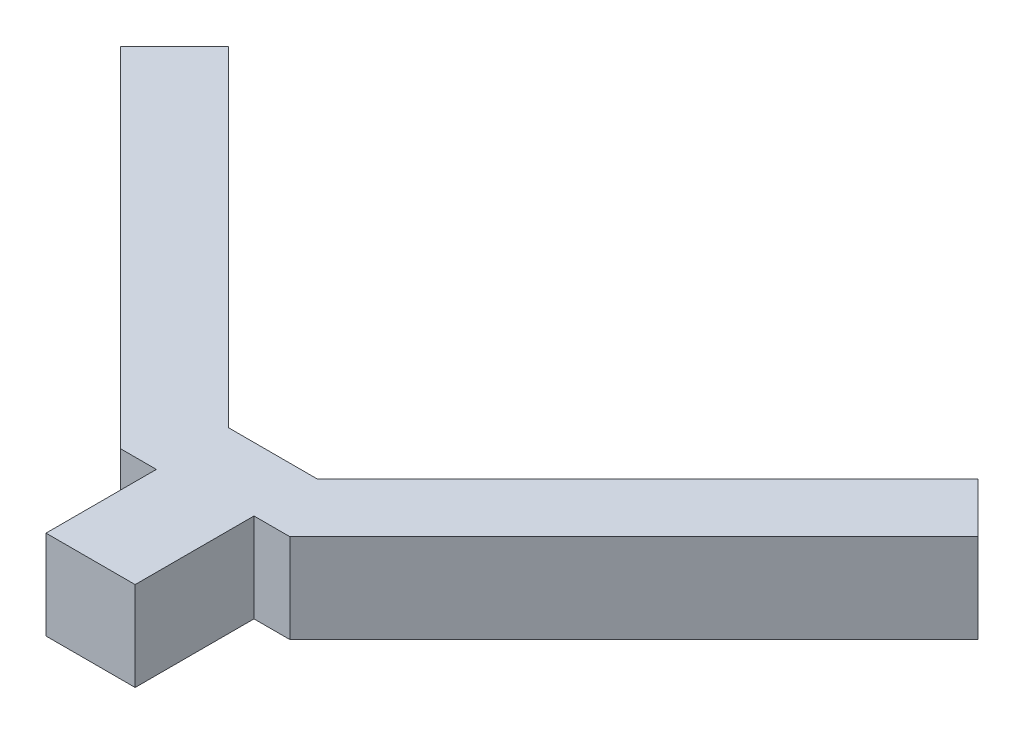
SolidWorks part; units mm, degrees
ref_plane "前视基准面" through (0, 0, 0) normal (0, 0, 1) x (1, 0, 0)
ref_plane "上视基准面" through (0, 0, 0) normal (0, 1, 0) x (1, 0, 0)
ref_plane "右视基准面" through (0, 0, 0) normal (1, 0, 0) x (0, 0, -1)
sketch "草图1" plane through (0, 0, 0) normal (0, 1, 0) x (1, 0, 0)
  line L0 (0.4355, 2.8768) -> (8.2137, 10.655)
  line L1 (8.2137, 10.655) -> (9.3865, 9.4822)
  line L2 (-1.6645, 1.1768) -> (-1.6645, -1.4232)
  line L3 (-1.6645, -1.4232) -> (0.4355, -1.4232)
  line L4 (0.4355, 1.3768) -> (0.4355, -1.4232)
  line L5 (-1.6645, 1.1768) -> (0.4355, -1.4232) construction
  line L6 (-1.6645, -1.4232) -> (0.4355, 1.3768) construction
  line L7 (-1.6645, 2.8768) -> (0.4355, 2.8768)
  line L8 (-1.6645, 2.8768) -> (-9.4427, 10.655)
  line L9 (-9.4427, 10.655) -> (-10.7155, 9.3822)
  line L11 (-10.7155, 9.3822) -> (-2.5101, 1.1768)
  line L12 (-2.5101, 1.1768) -> (-1.6645, 1.1768)
  line L13 (9.3865, 9.4822) -> (1.2811, 1.3768)
  line L14 (1.2811, 1.3768) -> (0.4355, 1.3768)
  point P4 (-0.6534, -0.075)
  dimension "D1" = 2.8
  dimension "D2" = 2.1
extrude "凸台-拉伸1" add sketch "草图1" along normal blind 2.1
